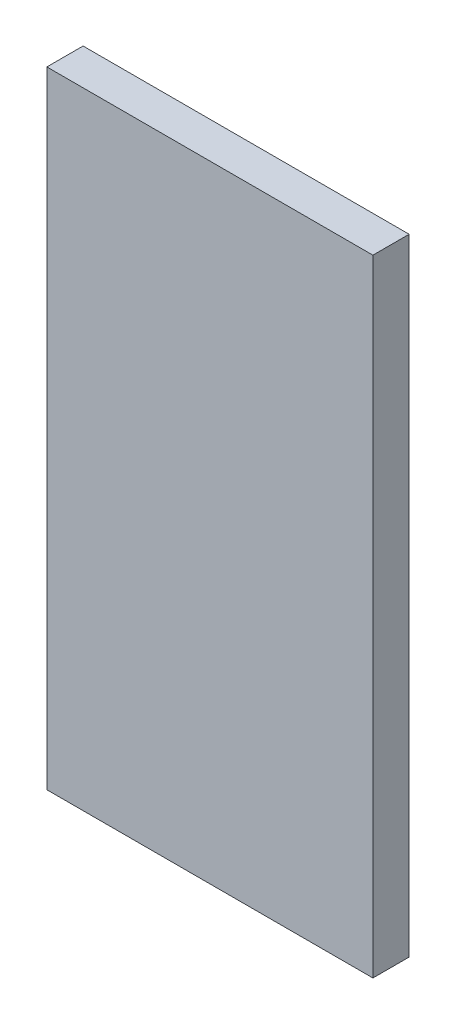
SolidWorks part; units mm, degrees
ref_plane "Front Plane" through (0, 0, 0) normal (0, 0, 1) x (1, 0, 0)
ref_plane "Top Plane" through (0, 0, 0) normal (0, 1, 0) x (1, 0, 0)
ref_plane "Right Plane" through (0, 0, 0) normal (1, 0, 0) x (0, 0, -1)
sketch "Sketch1" plane through (0, 0, 0) normal (0, 0, 1) x (1, 0, 0)
  line L1 (-20.0206, 24.7765) -> (37.1294, 24.7765)
  line L2 (-20.0206, 24.7765) -> (-20.0206, -46.8515)
  line L3 (-20.0206, -46.8515) -> (37.1294, -46.8515)
  line L4 (37.1294, 24.7765) -> (37.1294, -46.8515)
  dimension "D1" = 57.15
  dimension "D2" = 71.628
extrude "Boss-Extrude1" add sketch "Sketch1" along normal blind 6.35
sketch "Sketch2" plane through (0, 24.7765, 0) normal (0, 1, 0) x (1, 0, 0)
  line L4 (37.1294, 0) -> (-20.0206, 0)
  line L5 (-20.0206, 0) -> (-20.0206, -6.35)
  line L6 (-20.0206, -6.35) -> (37.1294, -6.35)
  line L7 (37.1294, -6.35) -> (37.1294, 0)
  line L8 (37.1294, 0) -> (-20.0206, 0)
  line L9 (-20.0206, 0) -> (-20.0206, -6.35)
  line L10 (-20.0206, -6.35) -> (37.1294, -6.35)
  line L11 (37.1294, -6.35) -> (37.1294, 0)
  dimension "D1" = 0
extrude "Boss-Extrude2" add sketch "Sketch2" along normal blind 38.1
